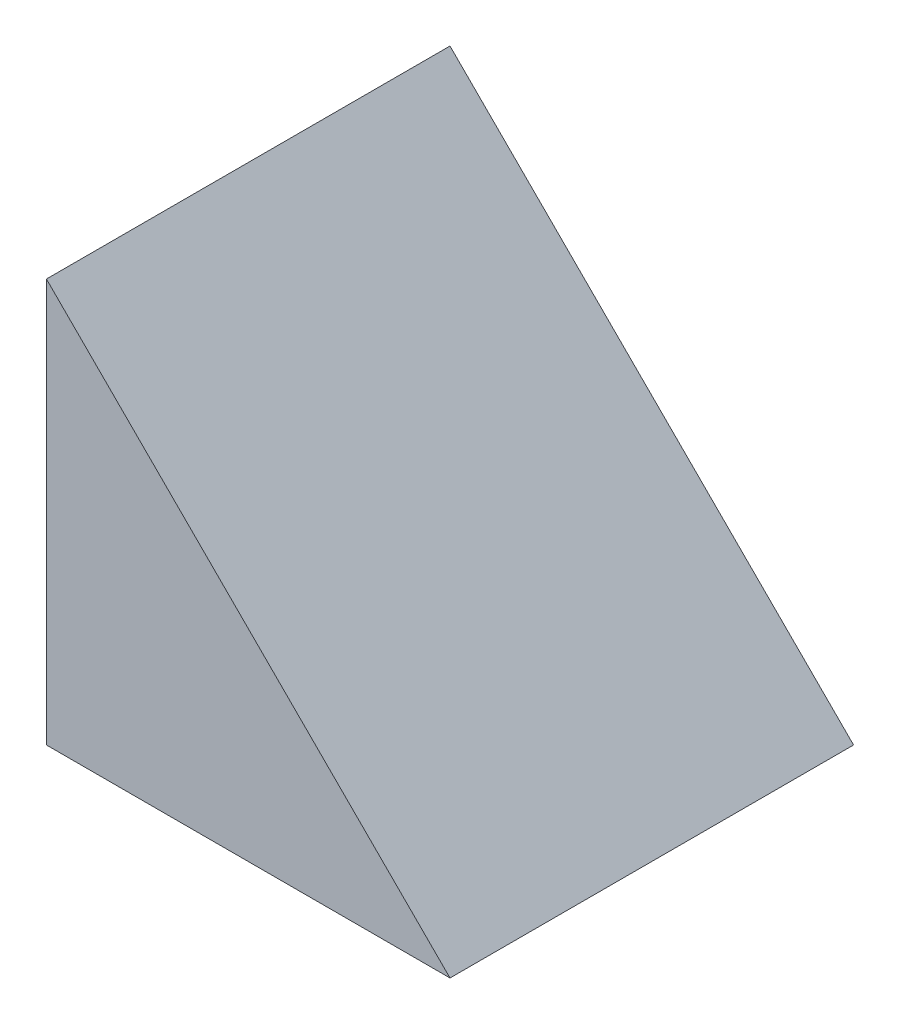
SolidWorks part; units mm, degrees
material "Acrílico (médio-alto impacto)"
ref_plane "Plano frontal" through (0, 0, 0) normal (0, 0, 1) x (1, 0, 0)
ref_plane "Plano superior" through (0, 0, 0) normal (0, 1, 0) x (1, 0, 0)
ref_plane "Plano direito" through (0, 0, 0) normal (1, 0, 0) x (0, 0, -1)
sketch "Esboço1" plane through (0, 0, 0) normal (0, 0, 1) x (1, 0, 0)
  line L0 (0, 0) -> (0, 15)
  line L1 (0, 15) -> (15, 0)
  line L2 (15, 0) -> (0, 0)
  dimension "D1" = 15
  dimension "D2" = 15
extrude "Ressalto-extrusão1" add sketch "Esboço1" along normal blind 15
